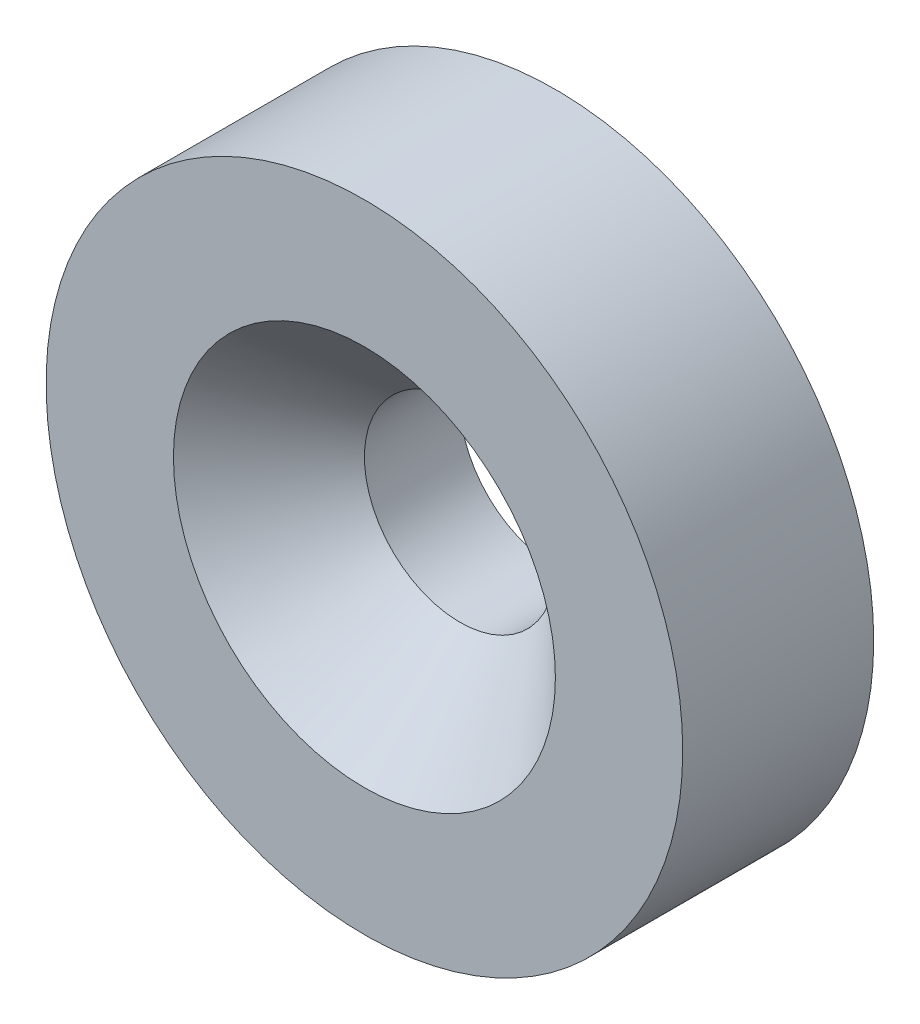
SolidWorks part; units mm, degrees
ref_plane "Front Plane" through (0, 0, 0) normal (0, 0, 1) x (1, 0, 0)
ref_plane "Top Plane" through (0, 0, 0) normal (0, 1, 0) x (1, 0, 0)
ref_plane "Right Plane" through (0, 0, 0) normal (1, 0, 0) x (0, 0, -1)
sketch "Sketch1" plane through (0, 0, 0) normal (0, 0, 1) x (1, 0, 0)
  circle A0 centre (0, 0) radius 5
  circle A1 centre (0, 0) radius 1.5
  dimension "D1" = 10
  dimension "D2" = 3
extrude "Boss-Extrude1" add sketch "Sketch1" along normal blind 3
chamfer "Chamfer1" distance 1.5 angle 45 1 edges at (1.5, 0, 3)
